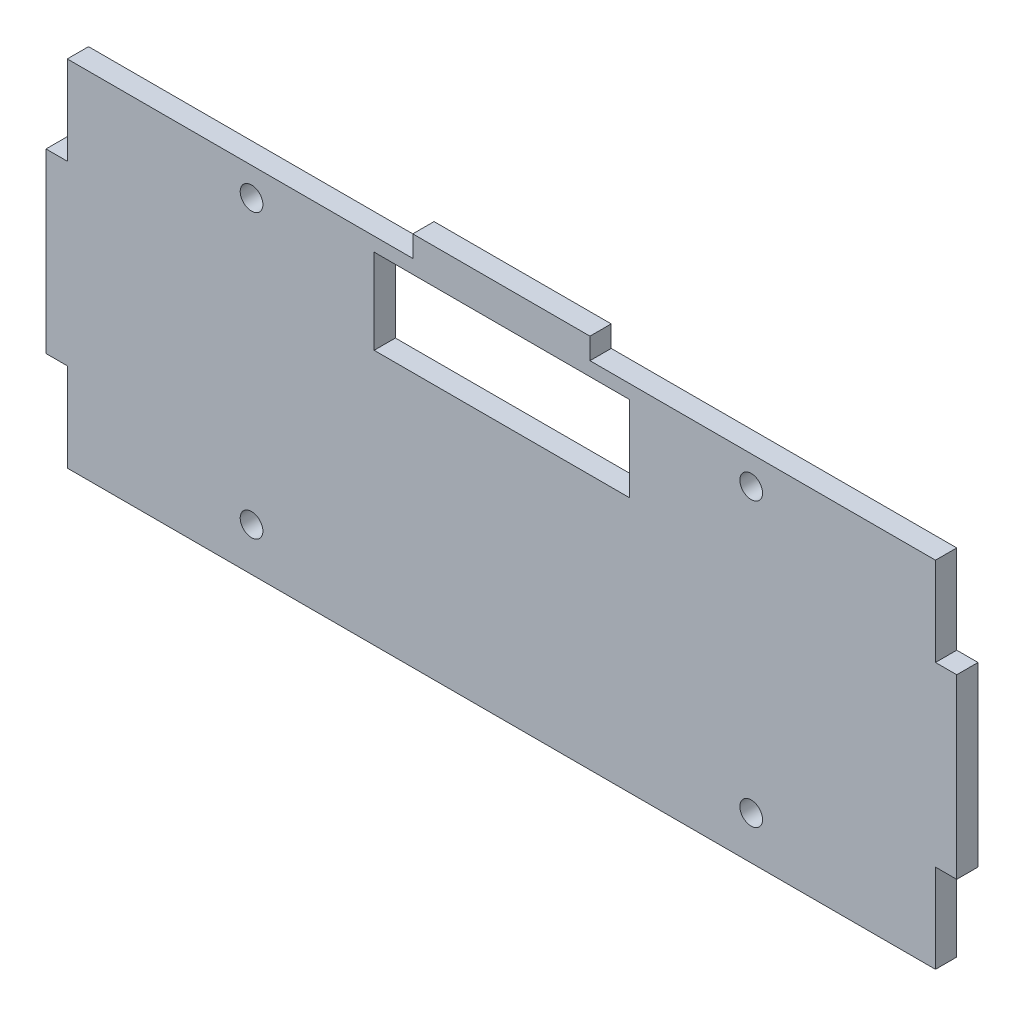
SolidWorks part; units mm, degrees
ref_plane "Plan de face" through (0, 0, 0) normal (0, 0, 1) x (1, 0, 0)
ref_plane "Plan de dessus" through (0, 0, 0) normal (0, 1, 0) x (1, 0, 0)
ref_plane "Plan de droite" through (0, 0, 0) normal (1, 0, 0) x (0, 0, -1)
sketch "Esquisse1" plane through (0, 0, 0) normal (0, 0, 1) x (1, 0, 0)
  line L28 (0, 45.0201) -> (0, -32.3311) construction
  line L29 (61.25, -25) -> (-61.25, -25)
  line L30 (61.25, -25) -> (61.25, -12.5)
  line L31 (61.25, 25) -> (29.85, 25)
  line L32 (-61.25, -25) -> (-61.25, -12.5)
  line L33 (61.25, -25) -> (-61.25, 25) construction
  line L34 (61.25, 25) -> (-61.25, -25) construction
  line L71 (61.25, 12.5) -> (64.25, 12.5)
  line L72 (-61.25, -12.5) -> (-64.25, -12.5)
  line L74 (-61.25, 12.5) -> (-64.25, 12.5)
  line L75 (-64.25, -12.5) -> (-64.25, 12.5)
  line L76 (64.25, -12.5) -> (64.25, 12.5)
  line L77 (61.25, -12.5) -> (64.25, -12.5)
  line L79 (-61.25, 12.5) -> (-61.25, 25)
  line L80 (61.25, 12.5) -> (61.25, 25)
  line L81 (26.65, 25) -> (12.5, 25)
  line L82 (-29.85, 25) -> (-61.25, 25)
  line L83 (-12.5, 25) -> (-26.65, 25)
  line L85 (-12.5, 25) -> (-12.5, 28)
  line L86 (-12.5, 28) -> (12.5, 28)
  line L87 (12.5, 25) -> (12.5, 28)
  line L88 (-29.85, 25) -> (-26.65, 25)
  line L89 (26.65, 25) -> (29.85, 25)
  point P0 (0, 0)
  point P44 (0, 28)
  dimension "D1" = 50
  dimension "D2" = 122.5
  dimension "D5" = 25
  dimension "D6" = 3
  dimension "D7" = 25
  dimension "D8" = 3
extrude "Boss.-Extru.1" add sketch "Esquisse1" along normal blind 3
sketch "Esquisse3" plane through (0, 0, 0) normal (0, 0, -1) x (-1, 0, 0)
  line L1 (-18.0477, 23.0436) -> (17.9523, 23.0436)
  line L2 (-18.0477, 23.0436) -> (-18.0477, 11.0436)
  line L3 (-18.0477, 11.0436) -> (17.9523, 11.0436)
  line L4 (17.9523, 23.0436) -> (17.9523, 11.0436)
  line L5 (-18.0477, 23.0436) -> (17.9523, 11.0436) construction
  line L6 (-18.0477, 11.0436) -> (17.9523, 23.0436) construction
  point P0 (-0.0477, 17.0436)
  dimension "D1" = 36
  dimension "D2" = 12
extrude "Enlèv. mat.-Extru.1" cut sketch "Esquisse3" against normal blind 4
sketch "Sketch1" plane through (0, 0, 3) normal (0, 0, 1) x (1, 0, 0)
  circle A0 centre (35.25, 21) radius 1.6
extrude "Cut-Extrude1" cut sketch "Sketch1" against normal through all
sketch "Sketch2" plane through (0, 0, 3) normal (0, 0, 1) x (1, 0, 0)
  circle A0 centre (-35.25, 21) radius 1.6
extrude "Cut-Extrude2" cut sketch "Sketch2" against normal through all
sketch "Sketch3" plane through (0, 0, 3) normal (0, 0, 1) x (1, 0, 0)
  circle A0 centre (-35.25, -18.9) radius 1.6
  circle A1 centre (35.25, -18.9) radius 1.6
extrude "Cut-Extrude3" cut sketch "Sketch3" against normal through all
